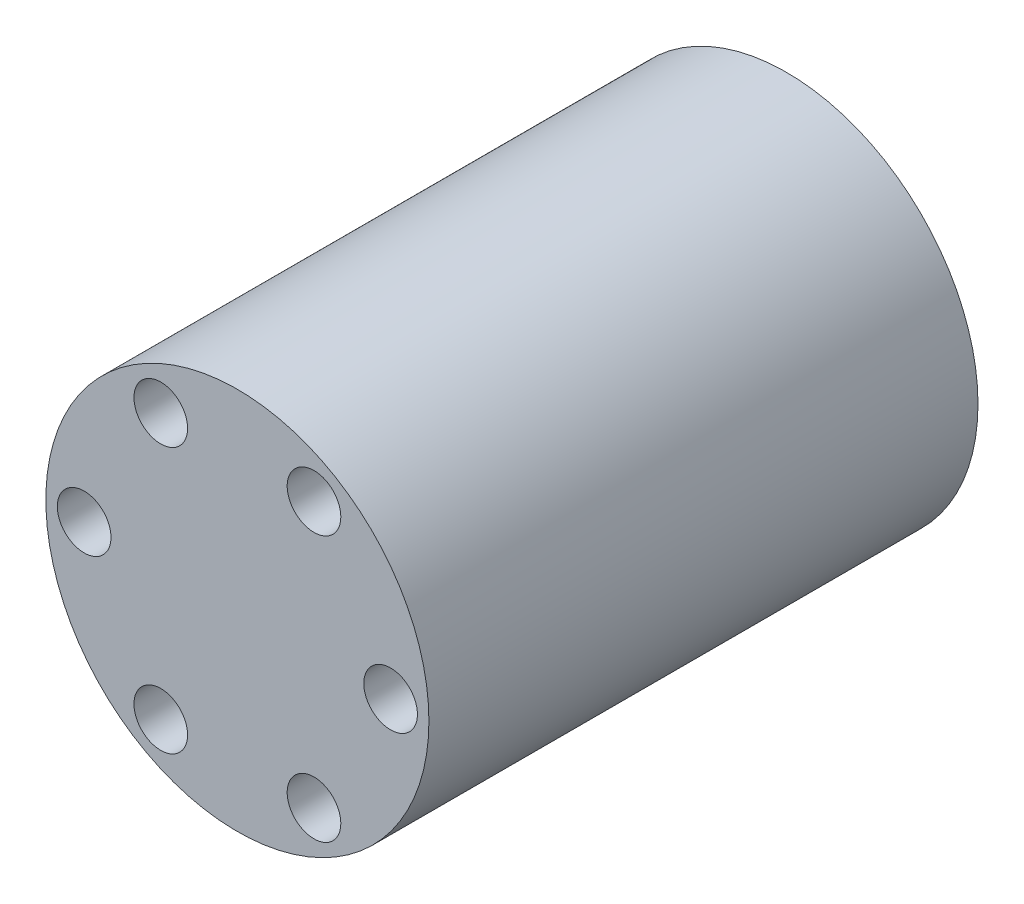
SolidWorks part; units mm, degrees
ref_plane "Front Plane" through (0, 0, 0) normal (0, 0, 1) x (1, 0, 0)
ref_plane "Top Plane" through (0, 0, 0) normal (0, 1, 0) x (1, 0, 0)
ref_plane "Right Plane" through (0, 0, 0) normal (1, 0, 0) x (0, 0, -1)
sketch "Sketch1" plane through (0, 0, 0) normal (0, 0, 1) x (1, 0, 0)
  circle A0 centre (0, 0) radius 15
  dimension "D1" = 30
extrude "Boss-Extrude1" add sketch "Sketch1" along normal mid plane 43 contours A0
sketch "Sketch2" plane through (0, 0, 21.5) normal (0, 0, 1) x (1, 0, 0)
  line L0 (0, 0) -> (-12, 0) construction
  circle A0 centre (-12, 0) radius 2.1
  circle A1 centre (-6, 10.3923) radius 2.1
  circle A2 centre (6, 10.3923) radius 2.1
  circle A3 centre (12, 0) radius 2.1
  circle A4 centre (6, -10.3923) radius 2.1
  circle A5 centre (-6, -10.3923) radius 2.1
  point P4 (-8.067, -12.4216)
  point P5 (0, 0)
  point P16 (0, 0)
  dimension "D2" = 4.2
  dimension "D1" = 12
  dimension "D3" = 6
extrude "Cut-Extrude1" cut sketch "Sketch2" against normal through all
